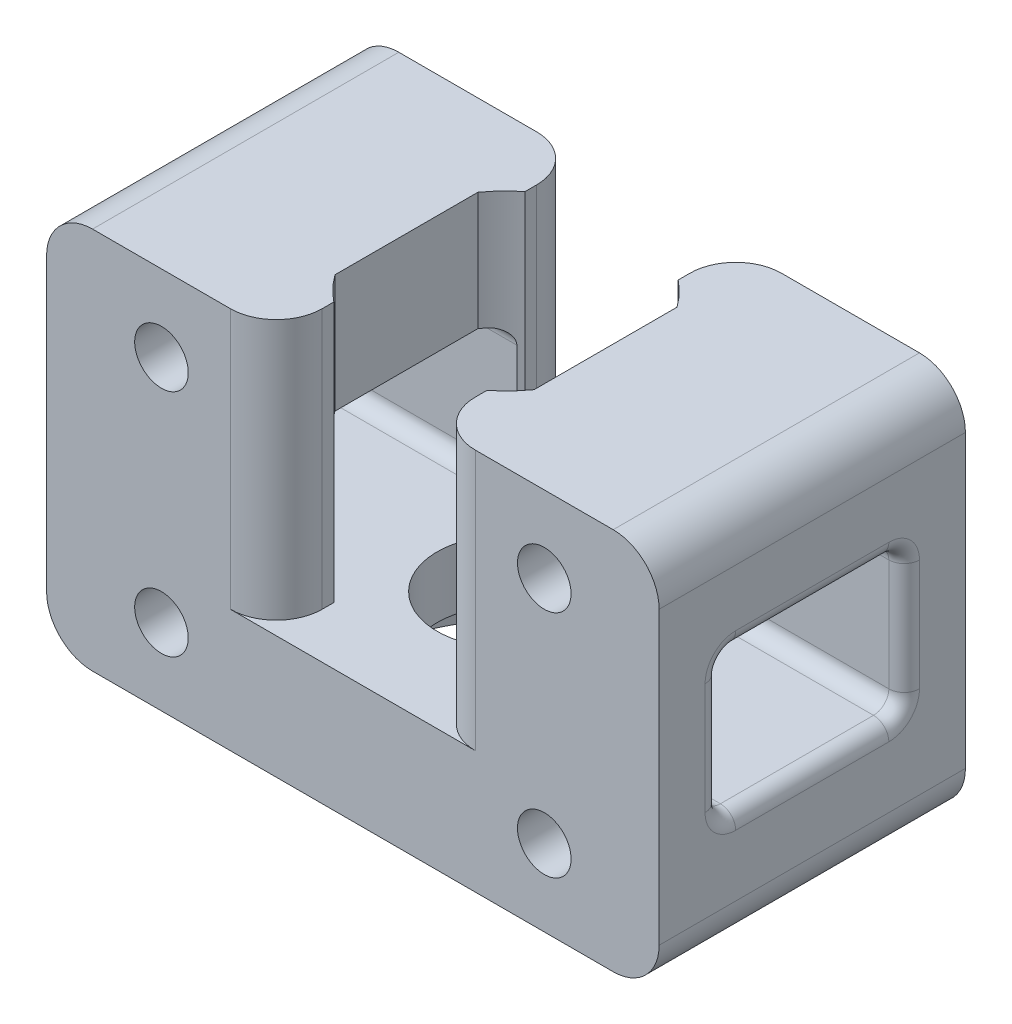
SolidWorks part; units mm, degrees
material "ABS"
ref_plane "前视基准面" through (0, 0, 0) normal (0, 0, 1) x (1, 0, 0)
ref_plane "上视基准面" through (0, 0, 0) normal (0, 1, 0) x (1, 0, 0)
ref_plane "右视基准面" through (0, 0, 0) normal (1, 0, 0) x (0, 0, -1)
sketch "草图1" plane through (0, 0, 0) normal (0, 0, 1) x (1, 0, 0)
  line L1 (0, 0) -> (40, 0)
  line L2 (0, 0) -> (0, 25)
  line L3 (0, 25) -> (40, 25)
  line L4 (40, 0) -> (40, 25)
  dimension "D1" = 25
  dimension "D2" = 40
extrude "凸台-拉伸1" add sketch "草图1" along normal blind 20
sketch "草图2" plane through (0, 25, 0) normal (0, 1, 0) x (1, 0, 0)
  line L0 (20, -10) -> (20, 0) construction
  line L1 (40, 0) -> (0, 0) construction
  line L2 (20, -10) -> (40, -10) construction
  line L3 (40, -20) -> (40, 0) construction
  circle A0 centre (20, -10) radius 4.5
  dimension "D1" = 9
extrude "切除-拉伸1" cut sketch "草图2" against normal through all
sketch "草图3" plane through (0, 25, 0) normal (0, 1, 0) x (1, 0, 0)
  line L0 (15.3363, -3.5) -> (24.6637, -3.5)
  line L5 (15.3363, -16.5) -> (24.6637, -16.5)
  line L6 (26.5, -5.3363) -> (26.5, -14.6637)
  line L7 (13.5, -5.3363) -> (13.5, -14.6637)
  circle A0 centre (20, -10) radius 8 construction
  arc A1 (13.5, -5.3363) -> (15.3363, -3.5) centre (20, -10) cw
  arc A2 (24.6637, -3.5) -> (26.5, -5.3363) centre (20, -10) cw
  arc A3 (13.5, -14.6637) -> (15.3363, -16.5) centre (20, -10) ccw
  arc A4 (26.5, -14.6637) -> (24.6637, -16.5) centre (20, -10) cw
  dimension "D3" = 16
  dimension "D1" = 13
  dimension "D2" = 13
extrude "切除-拉伸2" cut sketch "草图3" against normal blind 17
sketch "草图4" plane through (0, 0, 0) normal (0, 0, -1) x (-1, 0, 0)
  line L0 (-40, 0) -> (-40, 25) construction
  line L1 (0, 25) -> (0, 0) construction
  line L2 (-40, 25) -> (0, 25) construction
  line L3 (0, 0) -> (-40, 0) construction
  line L4 (-20, 8) -> (-20, 25) construction
  line L5 (-25, 25) -> (-15, 25)
  line L6 (-25, 25) -> (-25, 8)
  line L7 (-25, 8) -> (-15, 8)
  line L8 (-15, 25) -> (-15, 8)
  circle A0 centre (-32.5, 20) radius 1.75
  circle A1 centre (-32.5, 5) radius 1.75
  circle A2 centre (-7.5, 20) radius 1.75
  circle A3 centre (-7.5, 5) radius 1.75
  dimension "D1" = 3.5
  dimension "D2" = 3.5
  dimension "D3" = 3.5
  dimension "D4" = 3.5
  dimension "D5" = 7.5
  dimension "D6" = 7.5
  dimension "D7" = 7.5
  dimension "D8" = 7.5
  dimension "D9" = 5
  dimension "D10" = 5
  dimension "D11" = 5
  dimension "D12" = 5
  dimension "D13" = 17
  dimension "D14" = 10
extrude "切除-拉伸3" cut sketch "草图4" against normal through all
fillet "圆角1" radius 3 8 edges at (25, 16.5, 20) (15, 16.5, 20) (25, 16.5, 0) (15, 16.5, 0) (0, 25, 10) (40, 25, 10) (40, 0, 10) (0, 0, 10)
sketch "草图5" plane through (0, 0, 0) normal (0, -1, 0) x (1, 0, 0)
  circle A0 centre (20, 10) radius 9
  dimension "D1" = 18
extrude "切除-拉伸4" cut sketch "草图5" against normal blind 4
sketch "草图7" plane through (40, 0, 0) normal (1, 0, 0) x (0, 0, -1)
  line L0 (-20, 3) -> (-20, 22) construction
  line L1 (-16, 17.2877) -> (-4, 17.2877)
  line L2 (-16, 17.2877) -> (-16, 8)
  line L3 (-16, 8) -> (-4, 8)
  line L4 (-4, 17.2877) -> (-4, 8)
  line L5 (0, 3) -> (0, 22) construction
  line L6 (0, 0) -> (-20, 0) construction
  point P8 (-16, 8.6036)
  point P11 (-16, 19.4484)
  point P12 (-16, 17.1335)
  dimension "D1" = 4
  dimension "D2" = 4
  dimension "D3" = 8
extrude "切除-拉伸5" cut sketch "草图7" against normal through all
fillet "圆角2" radius 1 16 edges at (32.6458, 17.2877, 4) (7.3542, 17.2877, 4) (7.3542, 17.2877, 16) (32.6458, 17.2877, 16) (32.6458, 8, 4) (7.3542, 8, 4) (7.3542, 8, 16) (32.6458, 8, 16) (0, 17.2877, 10) (40, 12.6439, 4) (0, 12.6439, 16) (0, 12.6439, 4) (40, 17.2877, 10) (40, 8, 10) (0, 8, 10) (40, 12.6439, 16)
